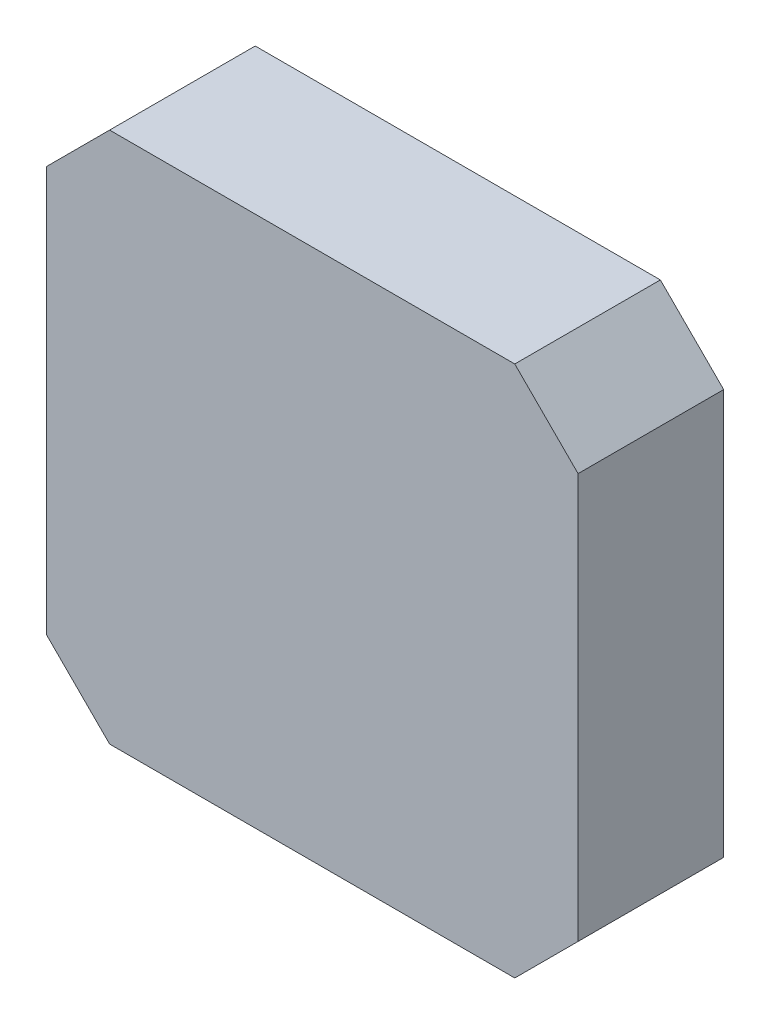
SolidWorks part; units mm, degrees
ref_plane "Front Plane" through (0, 0, 0) normal (0, 0, 1) x (1, 0, 0)
ref_plane "Top Plane" through (0, 0, 0) normal (0, 1, 0) x (1, 0, 0)
ref_plane "Right Plane" through (0, 0, 0) normal (1, 0, 0) x (0, 0, -1)
sketch "Sketch1" plane through (0, 0, 0) normal (0, 0, 1) x (1, 0, 0)
  line L1 (-21, 21) -> (21, 21)
  line L2 (-21, 21) -> (-21, -21)
  line L3 (-21, -21) -> (21, -21)
  line L4 (21, 21) -> (21, -21)
  line L5 (-21, 21) -> (21, -21) construction
  line L6 (-21, -21) -> (21, 21) construction
  circle A0 centre (0, 0) radius 19.75 construction
  dimension "D1" = 39.5
  dimension "D2" = 42
  dimension "D3" = 42
extrude "Boss-Extrude1" add sketch "Sketch1" along normal blind 11.5
chamfer "Chamfer1" distance 5 angle 45 4 edges at (-21, 21, 5.75) (21, 21, 5.75) (21, -21, 5.75) (-21, -21, 5.75)
